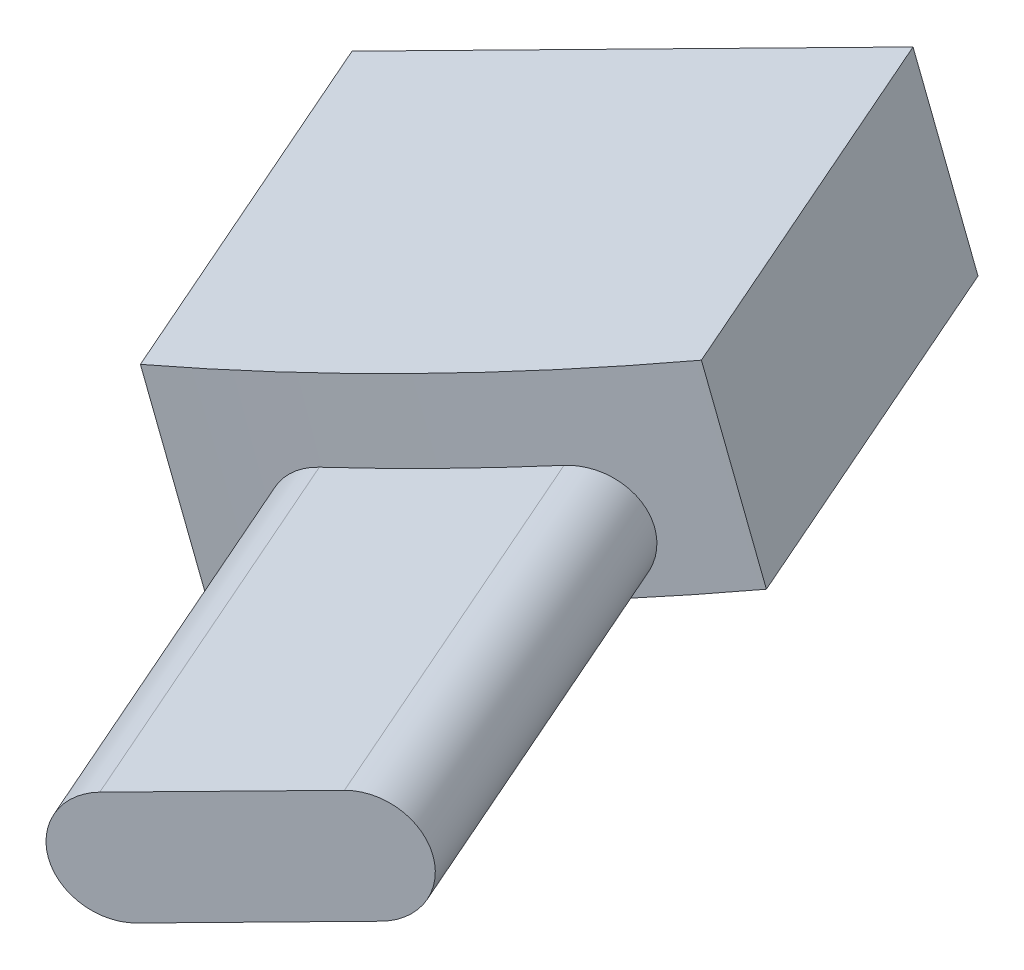
SolidWorks part; units mm, degrees
ref_plane "Front Plane" through (0, 0, 0) normal (0, 0, 1) x (1, 0, 0)
ref_plane "Top Plane" through (0, 0, 0) normal (0, 1, 0) x (1, 0, 0)
ref_plane "Right Plane" through (0, 0, 0) normal (1, 0, 0) x (0, 0, -1)
ref_plane "Plane1" through (-7.6077, 31.287, 3.3378) normal (-0.235, 0.9665, 0.1031) x (0.9719, 0.235, 0.0123)
sketch "Sketch2" plane through (-7.6077, 31.287, 3.3378) normal (-0.235, 0.9665, 0.1031) x (0.9719, 0.235, 0.0123)
  line L0 (8.9387, -72.6537) -> (-5.7589, -79.1022)
  line L3 (-5.7589, -79.1022) -> (0.2677, -92.8382)
  line L5 (14.9653, -86.3897) -> (8.9387, -72.6537)
  arc A1 (0.2677, -92.8382) -> (14.9653, -86.3897) centre (-16.2734, -35.1634) ccw construction
  arc A2 (0.2677, -92.8382) -> (14.9653, -86.3897) centre (-16.2734, -35.1634) ccw
  dimension "D2" = 8.025
  dimension "D1" = 15
  dimension "D3" = 15
extrude "Boss-Extrude1" add sketch "Sketch2" against normal blind 7
sketch "Sketch4" plane through (28.1738, 0, 64.2143) normal (-0.4018, 0, -0.9157) x (-0.9157, 0, 0.4018)
  line L0 (31.7251, 19.9991) -> (38.4907, 18.2027) construction
  line L1 (32.2384, 21.9322) -> (39.0039, 20.1357)
  line L2 (31.2118, 18.0661) -> (37.9774, 16.2697)
  line L3 (77.1555, 13.0057) -> (-60.5401, 49.5683) construction
  line L4 (35.1079, 19.1009) -> (34.5689, 17.0712) construction
  line L5 (26.8127, 19.1308) -> (42.3252, 15.0117) construction
  line L6 (31.7251, 19.9991) -> (27.3517, 21.1604) construction
  line L7 (38.4907, 18.2027) -> (42.8641, 17.0414) construction
  line L9 (44.1216, 21.7773) -> (28.6092, 25.8963)
  line L10 (28.6092, 25.8963) -> (26.8127, 19.1308)
  line L11 (26.8127, 19.1308) -> (42.3252, 15.0117)
  line L12 (42.3252, 15.0117) -> (44.1216, 21.7773)
  line L13 (44.1216, 21.7773) -> (28.6092, 25.8963) construction
  line L14 (28.6092, 25.8963) -> (26.8127, 19.1308) construction
  line L15 (26.8127, 19.1308) -> (42.3252, 15.0117) construction
  line L16 (42.3252, 15.0117) -> (44.1216, 21.7773) construction
  arc A0 (32.2384, 21.9322) -> (31.2118, 18.0661) centre (31.7251, 19.9991) ccw
  arc A1 (37.9774, 16.2697) -> (39.0039, 20.1357) centre (38.4907, 18.2027) ccw
  point P2 (35.1079, 19.1009)
  dimension "D1" = 2.1
  dimension "D4" = 7
  dimension "D2" = 0
  dimension "D3" = 4
extrude "Boss-Extrude2" add sketch "Sketch4" against normal blind 31
